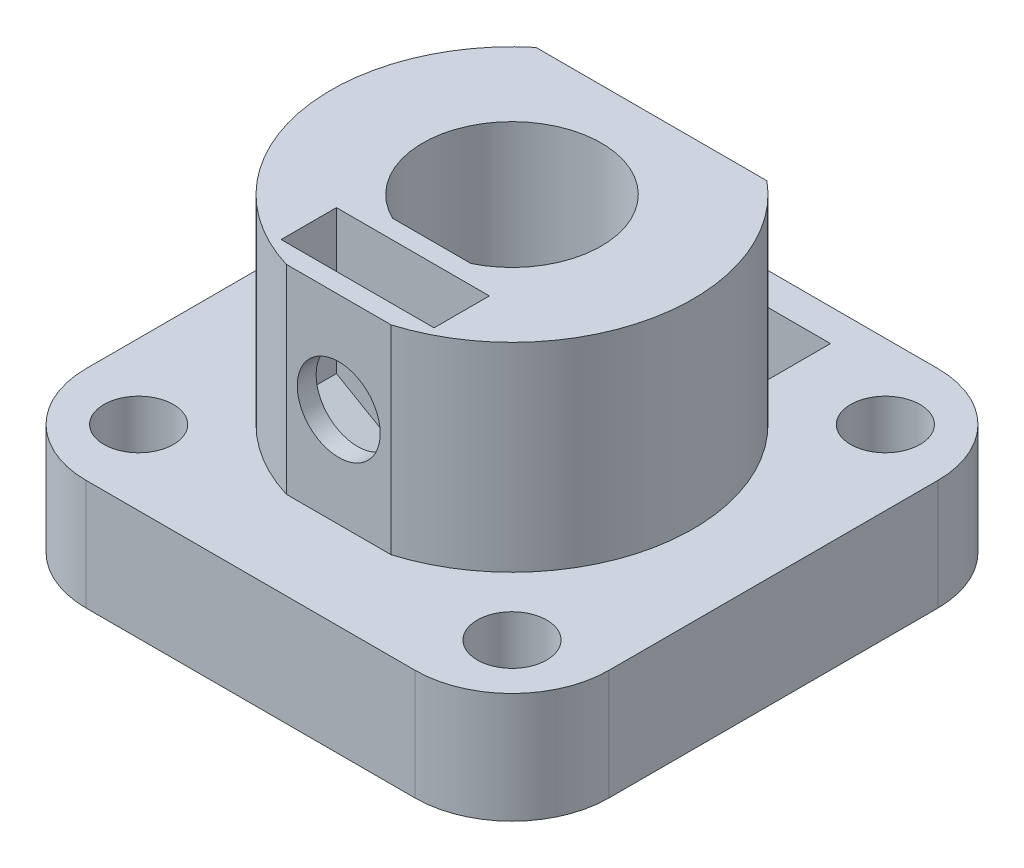
SolidWorks part; units mm, degrees
ref_plane "Front Plane" through (0, 0, 0) normal (0, 0, 1) x (1, 0, 0)
ref_plane "Top Plane" through (0, 0, 0) normal (0, 1, 0) x (1, 0, 0)
ref_plane "Right Plane" through (0, 0, 0) normal (1, 0, 0) x (0, 0, -1)
sketch "Sketch1" plane through (0, 0, 0) normal (0, 1, 0) x (1, 0, 0)
  line L1 (-9.45, -9.45) -> (9.45, -9.45)
  line L2 (-9.45, -9.45) -> (-9.45, 9.45)
  line L3 (-9.45, 9.45) -> (9.45, 9.45)
  line L4 (9.45, -9.45) -> (9.45, 9.45)
  line L5 (-9.45, -9.45) -> (9.45, 9.45) construction
  line L6 (-9.45, 9.45) -> (9.45, -9.45) construction
  line L7 (-6.75, -6.75) -> (6.75, -6.75)
  line L8 (-6.75, -6.75) -> (-6.75, 6.75)
  line L9 (-6.75, 6.75) -> (6.75, 6.75)
  line L10 (6.75, -6.75) -> (6.75, 6.75)
  line L11 (-6.75, -6.75) -> (6.75, 6.75) construction
  line L12 (-6.75, 6.75) -> (6.75, -6.75) construction
  circle A0 centre (-6.75, 6.75) radius 1.2551
  circle A1 centre (6.75, 6.75) radius 1.2551
  circle A2 centre (6.75, -6.75) radius 1.2551
  circle A3 centre (-6.75, -6.75) radius 1.2551
  point P0 (0, 0)
  point P6 (0, 0)
  dimension "D1" = 18.9
  dimension "D2" = 13.5
extrude "Boss-Extrude1" add sketch "Sketch1" along normal blind 4 contours L1 L4 L3 L2 A3 L8 A0 L9 A1 L10 A2 L7 | A3 L7 A2 L10 A1 L9 A0 L8
fillet "Fillet1" radius 3.5 4 edges at (9.45, 2, -9.45) (9.45, 2, 9.45) (-9.45, 2, 9.45) (-9.45, 2, -9.45)
sketch "Sketch2" plane through (0, 4, 0) normal (0, 1, 0) x (1, 0, 0)
  line L0 (9.45, 0) -> (-9.45, 0) construction
  line L1 (9.45, -5.95) -> (9.45, 5.95) construction
  line L2 (-9.45, -5.95) -> (-9.45, 5.95) construction
  line L3 (1.42, -2.9011) -> (-1.42, -2.9011)
  line L4 (-5.95, 9.45) -> (5.95, 9.45) construction
  line L5 (0, 9.45) -> (0, -9.45) construction
  line L6 (-5.95, -9.45) -> (5.95, -9.45) construction
  line L7 (1.8957, -6.2654) -> (-1.8957, -6.2654)
  line L8 (-6.75, -6.75) -> (0, 0) construction
  line L9 (-4.6287, -4.6287) -> (-6.75, -6.75) construction
  arc A0 (1.42, -2.9011) -> (-1.42, -2.9011) centre (0, 0) ccw
  arc A1 (1.8957, -6.2654) -> (-1.8957, -6.2654) centre (0, 0) ccw
  point P21 (-6.75, -6.75)
  dimension "D3" = 3.23
  dimension "D4" = 2.84
  dimension "D1" = 3
extrude "Boss-Extrude2" add sketch "Sketch2" along normal blind 7.2
sketch "Sketch3" plane through (0, 0, 6.2654) normal (0, 0, 1) x (1, 0, 0)
  line L0 (-1.8957, 11.2) -> (1.8957, 4) construction
  line L1 (1.8957, 4) -> (1.8957, 11.2) construction
  line L2 (1.8957, 11.2) -> (-1.8957, 4) construction
  circle A0 centre (0, 7.6) radius 1.5
  point P8 (0, 7.6)
  dimension "D1" = 3
extrude "Cut-Extrude1" cut sketch "Sketch3" against normal blind 7.2
ref_plane "Plane1" through (0, 0, 4.5833) normal (0, 0, -1) x (-1, 0, 0)
sketch "Sketch4" plane through (0, 0, 4.5833) normal (0, 0, -1) x (-1, 0, 0)
  line L0 (2.765, 9.1964) -> (2.765, 11.7232)
  line L1 (0, 4.4073) -> (2.765, 6.0036)
  line L2 (2.765, 6.0036) -> (2.765, 9.1964)
  line L3 (2.765, 9.1964) -> (0, 10.7927)
  line L4 (0, 10.7927) -> (-2.765, 9.1964)
  line L5 (-2.765, 9.1964) -> (-2.765, 6.0036)
  line L6 (-2.765, 6.0036) -> (0, 4.4073)
  line L7 (2.765, 11.7232) -> (-2.765, 11.7232)
  line L8 (-2.765, 11.7232) -> (-2.765, 9.1964)
  circle A0 centre (0, 7.6) radius 2.765 construction
  dimension "D1" = 5.53
ref_plane "Plane2" through (9.45, 4, 5.95) normal (0, 0, -1) x (-1, 0, 0)
extrude "Cut-Extrude2" cut sketch "Sketch4" against normal blind 1 and the other way blind 1 contours L5 L6 L1 L2 L3 L4 | L7 L8 L4 L3 L0
sketch "Sketch5" plane through (0, 4, 0) normal (0, 1, 0) x (1, 0, 0)
  line L0 (-1.42, -2.9011) -> (1.42, -2.9011)
  arc A0 (1.42, -2.9011) -> (-1.42, -2.9011) centre (0, 0) ccw
extrude "Cut-Extrude3" cut sketch "Sketch5" against normal up to surface (4 mm away) up to face at (-6.75, 0, -5.4949)
sketch "Sketch6" plane through (0, 11.2, 0) normal (0, 1, 0) x (1, 0, 0)
  line L1 (4.1759, 5.041) -> (-4.1759, 5.041)
  line L2 (4.1759, 5.041) -> (4.1759, 7.041)
  line L3 (4.1759, 7.041) -> (-4.1759, 7.041)
  line L4 (-4.1759, 5.041) -> (-4.1759, 7.041)
  arc A0 (1.8957, -6.2654) -> (-1.8957, -6.2654) centre (0, 0) ccw construction
  point P4 (4.6673, 5.0139)
  point P8 (-4.433, 5.2221)
  dimension "D1" = 2
extrude "Cut-Extrude4" cut sketch "Sketch6" against normal up to surface (7.2 mm away) up to face at (0, 4, 0)
sketch "Sketch7" plane through (0, 4, 0) normal (0, 1, 0) x (1, 0, 0)
  line L0 (4.1759, 5.041) -> (-4.1759, 5.041) construction
  line L1 (-2.776, 5.041) -> (3.2253, 5.041)
  line L2 (-2.776, 5.041) -> (-2.776, 8.2917)
  line L3 (-2.776, 8.2917) -> (3.2253, 8.2917)
  line L4 (3.2253, 5.041) -> (3.2253, 8.2917)
extrude "Cut-Extrude5" cut sketch "Sketch7" against normal up to surface (4 mm away) up to face at (0, 0, -0.1644)
